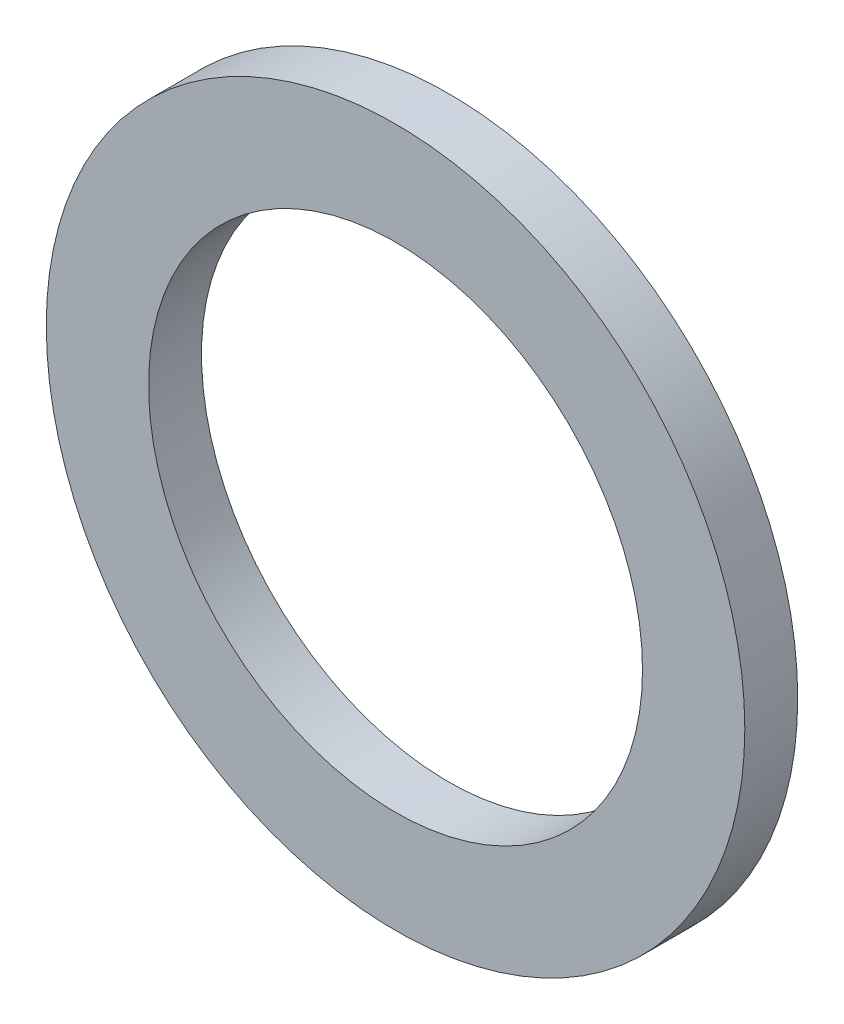
SolidWorks part; units mm, degrees
ref_plane "Plan1" through (0, 0, 0) normal (0, 0, 1) x (1, 0, 0)
ref_plane "Plan2" through (0, 0, 0) normal (0, 1, 0) x (1, 0, 0)
ref_plane "Plan3" through (0, 0, 0) normal (1, 0, 0) x (0, 0, -1)
sketch "Esquisse1" plane through (0, 0, 0) normal (0, 0, 1) x (1, 0, 0)
  circle A0 centre (0, 0) radius 7
  circle A1 centre (0, 0) radius 9.9
  dimension "D1" = 14
  dimension "D2" = 19.8
extrude "Base-Extrusion" add sketch "Esquisse1" along normal blind 1.5
